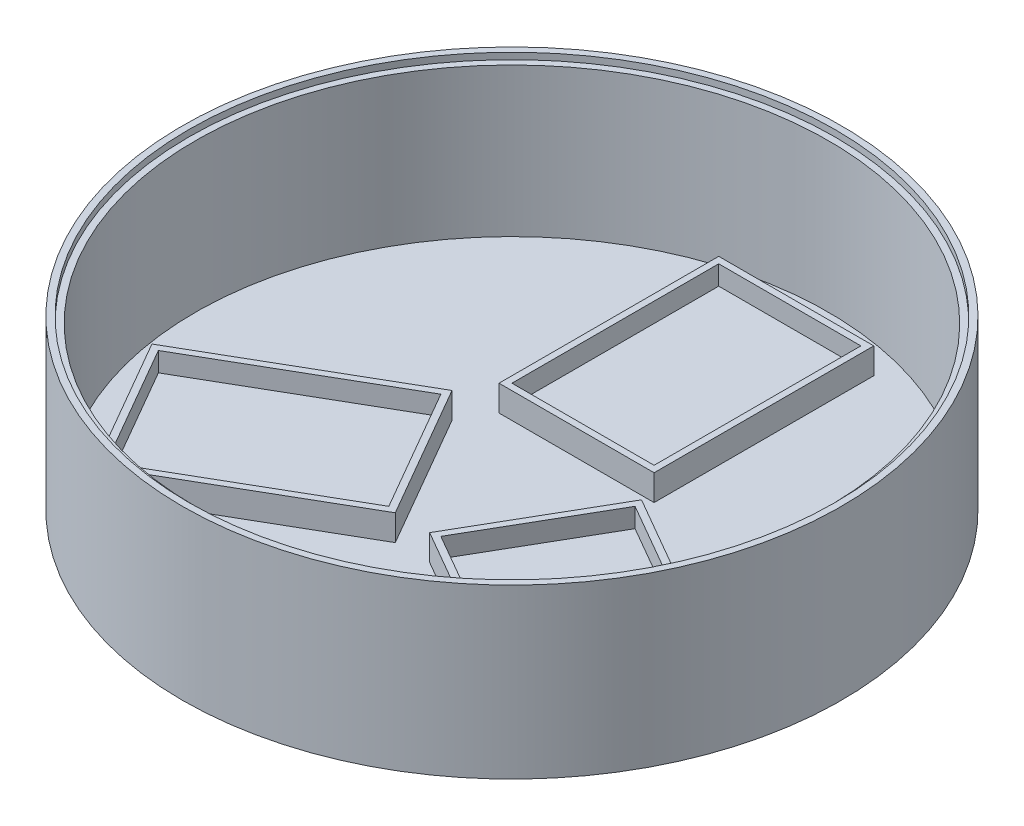
SolidWorks part; units mm, degrees
ref_plane "Front Plane" through (0, 0, 0) normal (0, 0, 1) x (1, 0, 0)
ref_plane "Top Plane" through (0, 0, 0) normal (0, 1, 0) x (1, 0, 0)
ref_plane "Right Plane" through (0, 0, 0) normal (1, 0, 0) x (0, 0, -1)
sketch "Sketch1" plane through (0, 0, 0) normal (0, 1, 0) x (1, 0, 0)
  circle A0 centre (0, 0) radius 255
  dimension "D1" = 510
extrude "Boss-Extrude1" add sketch "Sketch1" along normal blind 125
shell "Shell1" thickness 10
sketch "Sketch3" plane through (0, 10, 0) normal (0, 1, 0) x (1, 0, 0)
  line L0 (0, -55) -> (0, 55) construction
  line L1 (-60, 50) -> (60, 50)
  line L2 (-60, 50) -> (-60, 220)
  line L3 (-60, 220) -> (60, 220)
  line L4 (60, 50) -> (60, 220)
  line L5 (-60, 50) -> (60, 220) construction
  line L6 (-60, 220) -> (60, 50) construction
  line L8 (73.3013, 26.9615) -> (220.5256, -58.0385)
  line L9 (73.3013, 26.9615) -> (13.3013, -76.9615)
  line L10 (13.3013, -76.9615) -> (160.5256, -161.9615)
  line L11 (220.5256, -58.0385) -> (160.5256, -161.9615)
  line L12 (-13.3013, -76.9615) -> (-160.5256, -161.9615)
  line L13 (-13.3013, -76.9615) -> (-73.3013, 26.9615)
  line L14 (-73.3013, 26.9615) -> (-220.5256, -58.0385)
  line L15 (-160.5256, -161.9615) -> (-220.5256, -58.0385)
  circle A0 centre (0, 0) radius 245 construction
  point P0 (0, 135)
  point P19 (0, 0)
  dimension "D1" = 120
  dimension "D2" = 170
  dimension "D3" = 220
  dimension "D4" = 3
extrude "Boss-Extrude3" add sketch "Sketch3" along normal blind 20
sketch "Sketch2" plane through (0, 125, 0) normal (0, 1, 0) x (1, 0, 0)
  circle A1 centre (0, 0) radius 250
  circle A3 centre (0, 0) radius 255
  dimension "D2" = 500
  dimension "D3" = 510
extrude "Boss-Extrude2" add sketch "Sketch2" along normal blind 5
sketch "Sketch5" plane through (0, 30, 0) normal (0, 1, 0) x (1, 0, 0)
  line L4 (20.1314, -75.1314) -> (158.6955, -155.1314)
  line L5 (158.6955, -155.1314) -> (213.6955, -59.8686)
  line L6 (213.6955, -59.8686) -> (75.1314, 20.1314)
  line L7 (75.1314, 20.1314) -> (20.1314, -75.1314)
  line L8 (55, 55) -> (55, 215)
  line L9 (55, 215) -> (-55, 215)
  line L10 (-55, 215) -> (-55, 55)
  line L11 (-55, 55) -> (55, 55)
  line L12 (55, 55) -> (55, 215)
  line L13 (55, 215) -> (-55, 215)
  line L14 (-55, 215) -> (-55, 55)
  line L15 (-55, 55) -> (55, 55)
  line L16 (-75.1314, 20.1314) -> (-213.6955, -59.8686)
  line L17 (-213.6955, -59.8686) -> (-158.6955, -155.1314)
  line L18 (-158.6955, -155.1314) -> (-20.1314, -75.1314)
  line L19 (-20.1314, -75.1314) -> (-75.1314, 20.1314)
  point P15 (0, 0)
  dimension "D1" = 5
  dimension "D2" = 3
extrude "Cut-Extrude1" cut sketch "Sketch5" against normal blind 15
